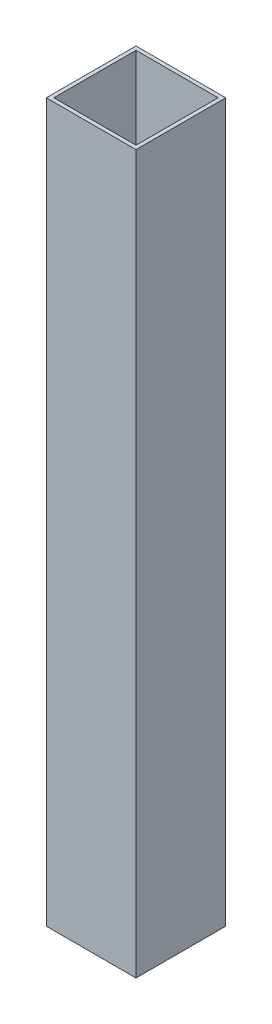
SolidWorks part; units mm, degrees
ref_plane "Front Plane" through (0, 0, 0) normal (0, 0, 1) x (1, 0, 0)
ref_plane "Top Plane" through (0, 0, 0) normal (0, 1, 0) x (1, 0, 0)
ref_plane "Right Plane" through (0, 0, 0) normal (1, 0, 0) x (0, 0, -1)
sketch "Sketch1" plane through (0, 0, 0) normal (0, 1, 0) x (1, 0, 0)
  line L0 (17.4625, 17.4625) -> (-17.4625, 17.4625)
  line L1 (19.05, 19.05) -> (-19.05, 19.05)
  line L2 (19.05, 19.05) -> (19.05, -19.05)
  line L3 (19.05, -19.05) -> (-19.05, -19.05)
  line L4 (-19.05, 19.05) -> (-19.05, -19.05)
  line L5 (19.05, 19.05) -> (-19.05, -19.05) construction
  line L6 (19.05, -19.05) -> (-19.05, 19.05) construction
  line L7 (-17.4625, 17.4625) -> (-17.4625, -17.4625)
  line L8 (17.4625, -17.4625) -> (-17.4625, -17.4625)
  line L9 (17.4625, 17.4625) -> (17.4625, -17.4625)
  point P0 (0, 0)
  dimension "D1" = 38.1
  dimension "D2" = 1.5875
extrude "Boss-Extrude1" add sketch "Sketch1" along normal blind 304.8
equation "\"WallThickness\"= 0.0625"
equation "\"TubeWidth\"= 1.5"
equation "\"Length\"= 12"
equation "\"D2@Sketch1\"=\"WallThickness\""
equation "\"D1@Sketch1\"=\"TubeWidth\""
